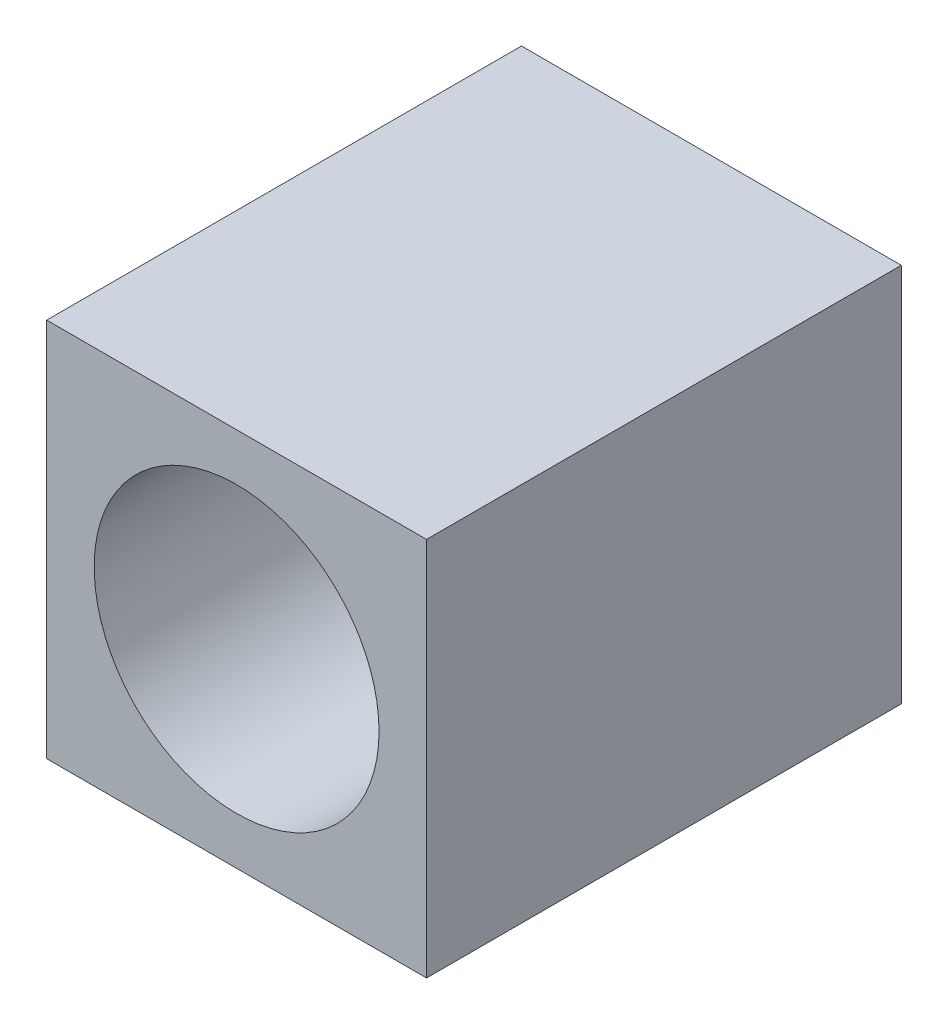
SolidWorks part; units mm, degrees
ref_plane "Front Plane" through (0, 0, 0) normal (0, 0, 1) x (1, 0, 0)
ref_plane "Top Plane" through (0, 0, 0) normal (0, 1, 0) x (1, 0, 0)
ref_plane "Right Plane" through (0, 0, 0) normal (1, 0, 0) x (0, 0, -1)
sketch "Sketch2" plane through (0, 0, 0) normal (0, 0, 1) x (1, 0, 0)
  line L1 (-20, -20) -> (20, -20)
  line L2 (-20, -20) -> (-20, 20)
  line L3 (-20, 20) -> (20, 20)
  line L4 (20, -20) -> (20, 20)
  line L5 (-20, -20) -> (20, 20) construction
  line L6 (-20, 20) -> (20, -20) construction
  circle A0 centre (0, 0) radius 15
  dimension "D1" = 30
  dimension "D2" = 40
  dimension "D3" = 40
extrude "Boss-Extrude1" add sketch "Sketch2" along normal blind 50
